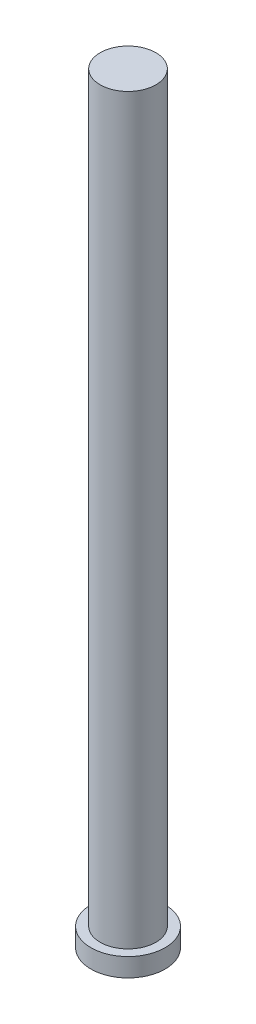
SolidWorks part; units mm, degrees
ref_plane "Front Plane" through (0, 0, 0) normal (0, 0, 1) x (1, 0, 0)
ref_plane "Top Plane" through (0, 0, 0) normal (0, 1, 0) x (1, 0, 0)
ref_plane "Right Plane" through (0, 0, 0) normal (1, 0, 0) x (0, 0, -1)
sketch "Sketch1" plane through (0, 0, 0) normal (0, 1, 0) x (1, 0, 0)
  circle A0 centre (0, 0) radius 1.5
  dimension "D1" = 3
extrude "Boss-Extrude1" add sketch "Sketch1" along normal blind 40
sketch "Sketch2" plane through (0, 0, 0) normal (0, -1, 0) x (1, 0, 0)
  circle A0 centre (0, 0) radius 2
  dimension "D1" = 4
extrude "Boss-Extrude2" add sketch "Sketch2" along normal blind 1
